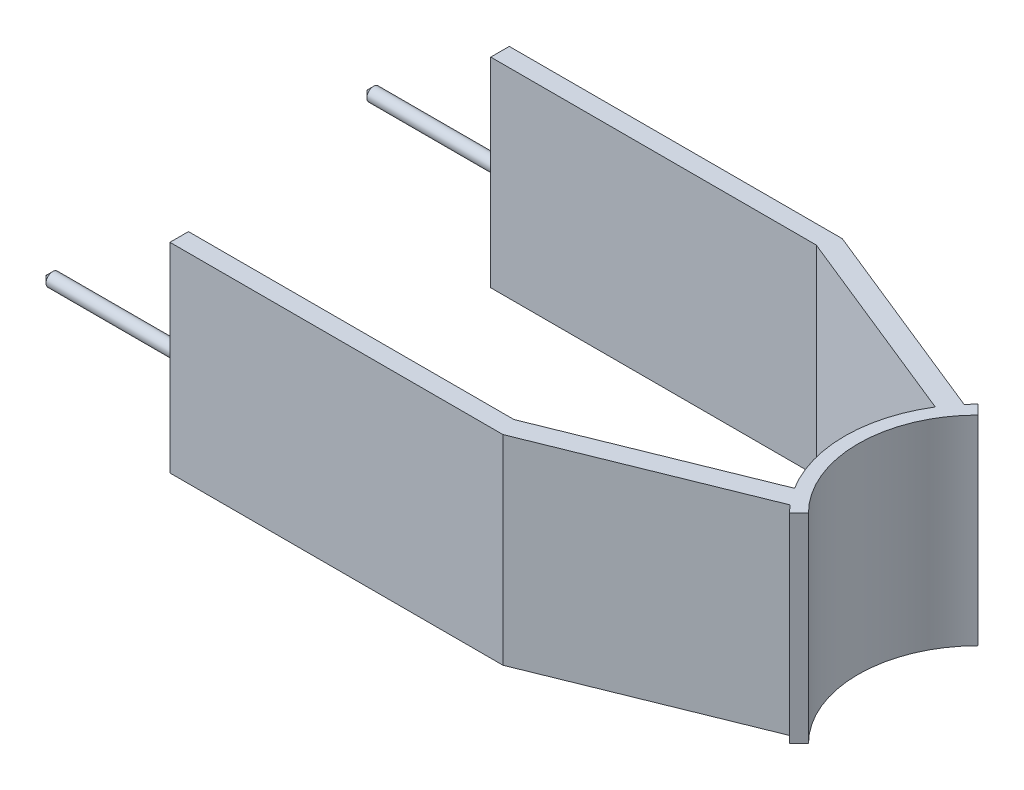
SolidWorks part; units mm, degrees
material "AISI 304"
ref_plane "Front Plane" through (0, 0, 0) normal (0, 0, 1) x (1, 0, 0)
ref_plane "Top Plane" through (0, 0, 0) normal (0, 1, 0) x (1, 0, 0)
ref_plane "Right Plane" through (0, 0, 0) normal (1, 0, 0) x (0, 0, -1)
sketch "Sketch5" plane through (0, 0, 0) normal (0, 1, 0) x (1, 0, 0)
  line L0 (-12.7279, 12.7279) -> (-14.1421, 14.1421)
  line L2 (-14.1421, -14.1421) -> (-12.7279, -12.7279)
  arc A0 (-14.1421, 14.1421) -> (-14.1421, -14.1421) centre (0, 0) ccw
  arc A1 (-12.7279, 12.7279) -> (-12.7279, -12.7279) centre (0, 0) ccw
  dimension "D1" = 40
  dimension "D2" = 36
  dimension "D3" = 12.7279
extrude "Boss-Extrude2" add sketch "Sketch5" along normal blind 30
sketch "Sketch12" plane through (0, 30, 0) normal (0, 1, 0) x (1, 0, 0)
  line L2 (-16.9797, 10.5684) -> (-46.9797, 22.6934)
  line L3 (-46.9797, 22.6934) -> (-45.8555, 25.4748)
  line L4 (-45.8555, 25.4748) -> (-15.1449, 13.0626)
  line L5 (-12.7279, 12.7279) -> (-14.1421, 14.1421)
  line L6 (-14.1421, -14.1421) -> (-12.7279, -12.7279)
  line L7 (-12.7279, 12.7279) -> (-14.1421, 14.1421)
  line L8 (-14.1421, -14.1421) -> (-12.7279, -12.7279)
  arc A1 (-14.1421, 14.1421) -> (-14.1421, -14.1421) centre (0, 0) ccw construction
  arc A3 (-14.1421, 14.1421) -> (-15.1449, 13.0626) centre (0, 0) ccw
  arc A5 (-12.7279, 12.7279) -> (-12.7279, -12.7279) centre (0, 0) ccw
  arc A6 (-14.1421, 14.1421) -> (-14.1421, -14.1421) centre (0, 0) ccw
  arc A7 (-12.7279, 12.7279) -> (-12.7279, -12.7279) centre (0, 0) ccw
  arc A8 (-16.9797, 10.5684) -> (-14.1421, -14.1421) centre (0, 0) ccw
  dimension "D1" = 3
  dimension "D2" = 30
  dimension "D3" = 30.7106
  dimension "D4" = 6.4358
  dimension "D5" = 0
extrude "Boss-Extrude3" add sketch "Sketch12" against normal blind 30
ref_plane "Plane1" through (0, 0, 0) normal (0, 0, -1) x (-1, 0, 0)
sketch "Sketch14" plane through (0, 30, 0) normal (0, 1, 0) x (1, 0, 0)
  line L0 (-45.8555, 25.4748) -> (-95.8555, 25.4748)
  line L1 (-46.9797, 22.6934) -> (-95.8555, 22.6934)
  line L2 (-95.8555, 22.6934) -> (-95.8555, 25.4748)
  line L11 (-15.1449, 13.0626) -> (-45.8555, 25.4748)
  line L12 (-45.8555, 25.4748) -> (-46.9797, 22.6934)
  line L13 (-46.9797, 22.6934) -> (-16.9797, 10.5684)
  line L17 (-14.1421, -14.1421) -> (-12.7279, -12.7279)
  line L18 (-12.7279, 12.7279) -> (-14.1421, 14.1421)
  line L20 (-45.8555, 25.4748) -> (-46.9797, 22.6934)
  arc A4 (-14.1421, 14.1421) -> (-15.1449, 13.0626) centre (0, 0) ccw
  arc A5 (-16.9797, 10.5684) -> (-14.1421, -14.1421) centre (0, 0) ccw
  arc A7 (-12.7279, 12.7279) -> (-12.7279, -12.7279) centre (0, 0) ccw
  dimension "D1" = 50
  dimension "D2" = 0
extrude "Boss-Extrude4" add sketch "Sketch14" against normal blind 30
mirror "Mirror1" about plane through (0, 0, 0) normal (0, 0, -1) of "Boss-Extrude4", "Boss-Extrude3"
sketch "Sketch15" plane through (-95.8555, 0, 0) normal (-1, 0, 0) x (0, 0, 1)
  line L0 (25.4748, 30) -> (22.6934, 30) construction
  circle A0 centre (24.0841, 15) radius 1
  dimension "D1" = 2
  dimension "D2" = 15
extrude "Boss-Extrude5" add sketch "Sketch15" along normal blind 20
cosmetic thread "Cosmetic Thread2" parameters "D1"=19, "D2"=1
chamfer "Chamfer1" distance 1 angle 45 1 edges at (-115.8555, 15, 25.0841)
mirror "Mirror2" about plane through (0, 0, 0) normal (0, 0, -1) of "Boss-Extrude5", "Chamfer1"
cosmetic thread "Cosmetic Thread3" parameters "D1"=19, "D2"=1
